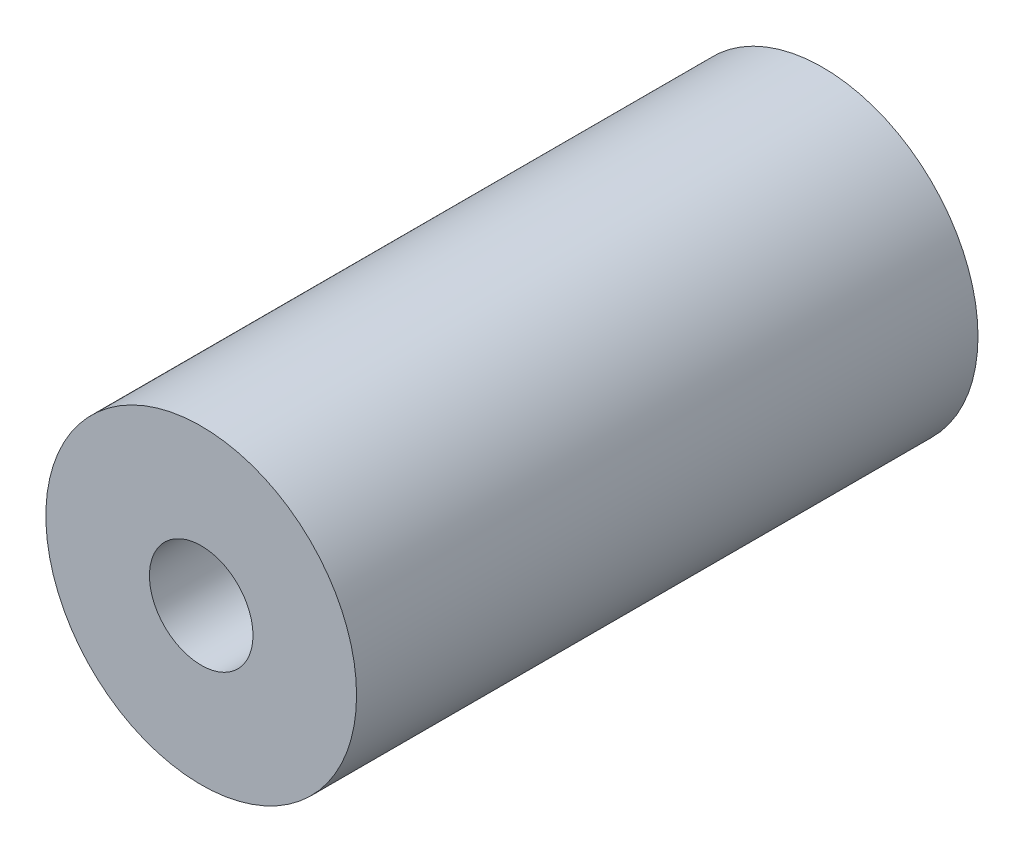
SolidWorks part; units mm, degrees
ref_plane "Front Plane" through (0, 0, 0) normal (0, 0, 1) x (1, 0, 0)
ref_plane "Top Plane" through (0, 0, 0) normal (0, 1, 0) x (1, 0, 0)
ref_plane "Right Plane" through (0, 0, 0) normal (1, 0, 0) x (0, 0, -1)
sketch "Sketch1" plane through (0, 0, 0) normal (0, 0, 1) x (1, 0, 0)
  circle A0 centre (0, 0) radius 15
  circle A1 centre (0, 0) radius 5
  dimension "D1" = 10
  dimension "D2" = 30
extrude "Boss-Extrude1" add sketch "Sketch1" against normal blind 60
